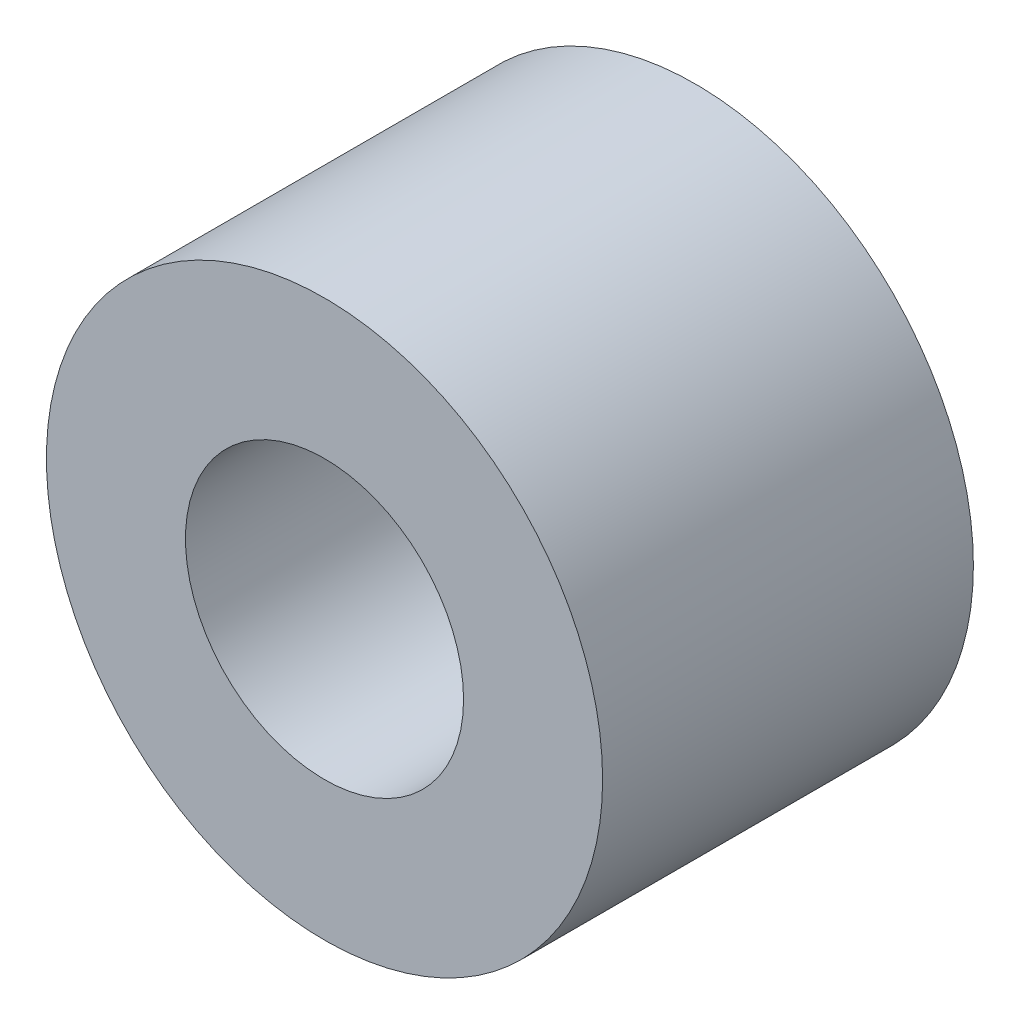
SolidWorks part; units mm, degrees
ref_plane "Front Plane" through (0, 0, 0) normal (0, 0, 1) x (1, 0, 0)
ref_plane "Top Plane" through (0, 0, 0) normal (0, 1, 0) x (1, 0, 0)
ref_plane "Right Plane" through (0, 0, 0) normal (1, 0, 0) x (0, 0, -1)
sketch "Sketch1" plane through (0, 0, 0) normal (0, 0, 1) x (1, 0, 0)
  circle A0 centre (0, 0) radius 1.5
  circle A1 centre (0, 0) radius 0.75
  dimension "D1" = 3
  dimension "D2" = 1.5
extrude "Boss-Extrude1" add sketch "Sketch1" along normal blind 2
sketch "Sketch2" plane through (0, 0, 2) normal (0, 0, 1) x (1, 0, 0)
  circle A0 centre (0, 0) radius 0.3
  circle A1 centre (0, 0) radius 1.5
  dimension "D1" = 3
